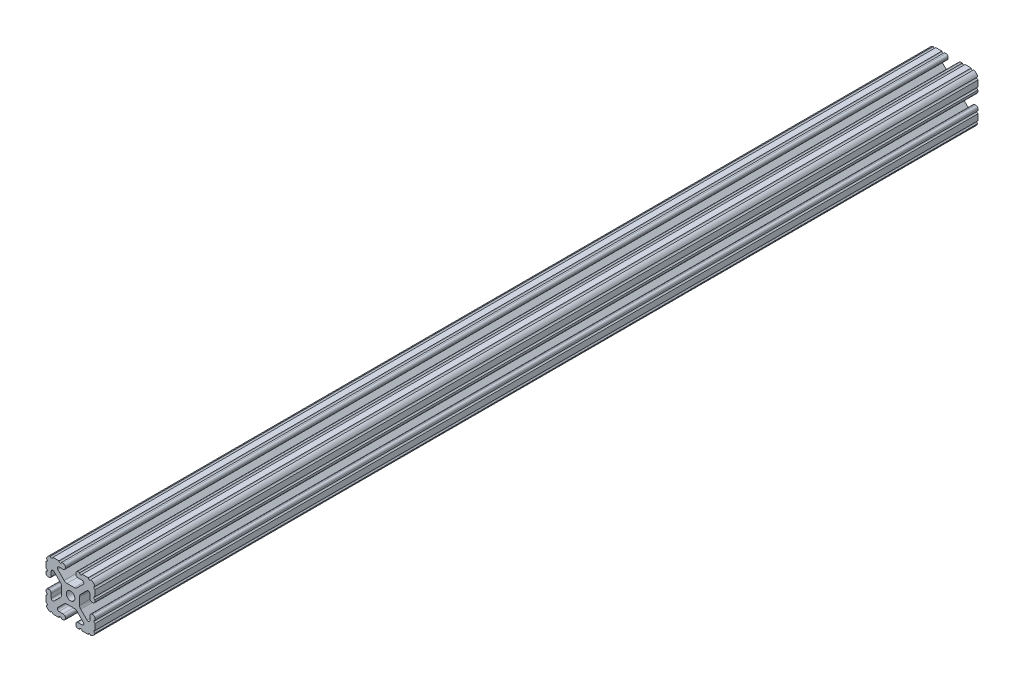
SolidWorks part; units mm, degrees
ref_plane "Front Plane" through (0, 0, 0) normal (0, 0, 1) x (1, 0, 0)
ref_plane "Top Plane" through (0, 0, 0) normal (0, 1, 0) x (1, 0, 0)
ref_plane "Right Plane" through (0, 0, 0) normal (1, 0, 0) x (0, 0, -1)
sketch "Sketch2" plane through (0, 0, 0) normal (0, 0, 1) x (1, 0, 0)
  line L0 (0, 19.05) -> (0, -19.05) construction
  line L1 (-19.05, 0) -> (19.05, 0) construction
  line L2 (4.064, -19.05) -> (19.05, -19.05)
  line L3 (19.05, -19.05) -> (19.05, -4.064)
  line L4 (4.064, -19.05) -> (4.064, -14.986)
  line L5 (4.064, -14.986) -> (12.1123, -14.986)
  line L6 (12.1123, -14.986) -> (4.1113, -6.985)
  line L7 (0, 0) -> (19.05, -19.05) construction
  line L8 (19.05, -4.064) -> (14.986, -4.064)
  line L9 (14.986, -4.064) -> (14.986, -12.1123)
  line L10 (14.986, -12.1123) -> (6.985, -4.1113)
  circle A0 centre (0, 0) radius 3.3274
  arc A1 (8.9963, -14.986) -> (9.909, -12.7826) centre (8.9963, -13.6953) ccw construction
  point P8 (0, -6.985)
  dimension "Center Hole Diameter" = 6.6548
  dimension "Rail Height" = 38.1
  dimension "Rail Width" = 38.1
  dimension "T-Slot Width" = 8.128
  dimension "Slot Inner Width" = 20.574
  dimension "Thickness" = 4.064
  dimension "Slot Depth" = 8.001
  dimension "D1" = 4.064
sketch "Sketch3" plane through (0, 0, 0) normal (1, 0, 0) x (0, 0, -1)
  line L0 (-342.5, -19.05) -> (342.5, -19.05) construction
  line L1 (-317.1, 0) -> (317.1, 0) construction
  dimension "Length" = 685
  dimension "D1" = 25.4
sketch "Sketch4" plane through (0, 0, 0) normal (0, 0, 1) x (1, 0, 0)
  line L0 (5.7912, -19.05) -> (14.3002, -19.05)
  line L1 (4.064, -19.05) -> (19.05, -19.05) construction
  line L2 (4.064, -19.05) -> (4.064, -14.986) construction
  line L3 (4.064, -14.986) -> (12.1123, -14.986) construction
  line L4 (4.064, -16.7132) -> (4.064, -17.3228)
  line L5 (5.7912, -14.986) -> (8.9963, -14.986)
  line L6 (0, -6.985) -> (2.833, -6.985)
  line L7 (12.1123, -14.986) -> (4.1113, -6.985) construction
  line L8 (5.0152, -7.8889) -> (9.909, -12.7826)
  line L9 (19.05, -19.05) -> (19.05, -4.064) construction
  line L10 (14.986, -12.1123) -> (6.985, -4.1113) construction
  line L11 (14.986, -4.064) -> (14.986, -12.1123) construction
  line L12 (14.986, -8.9963) -> (14.986, -5.7912)
  line L13 (19.05, -4.064) -> (14.986, -4.064) construction
  line L14 (16.7132, -4.064) -> (17.3228, -4.064)
  line L15 (19.05, -5.7912) -> (19.05, -14.3002)
  line L16 (12.7826, -9.909) -> (7.8889, -5.0152)
  line L17 (6.985, 0) -> (6.985, -2.833)
  line L18 (-19.05, 0) -> (19.05, 0) construction
  line L19 (0, -6.985) -> (0, -3.3274)
  line L20 (0, 19.05) -> (0, -19.05) construction
  line L21 (6.985, 0) -> (3.3274, 0)
  arc A0 (4.064, -17.3228) -> (5.7912, -19.05) centre (5.7912, -17.3228) ccw
  arc A2 (4.064, -16.7132) -> (5.7912, -14.986) centre (5.7912, -16.7132) cw
  arc A3 (8.9963, -14.986) -> (9.909, -12.7826) centre (8.9963, -13.6953) ccw
  arc A4 (2.833, -6.985) -> (5.0152, -7.8889) centre (2.833, -10.0711) cw
  arc A5 (14.3002, -19.05) -> (19.05, -14.3002) centre (14.3002, -14.3002) ccw
  arc A6 (12.7826, -9.909) -> (14.986, -8.9963) centre (13.6953, -8.9963) ccw
  arc A7 (14.986, -5.7912) -> (16.7132, -4.064) centre (16.7132, -5.7912) cw
  arc A8 (17.3228, -4.064) -> (19.05, -5.7912) centre (17.3228, -5.7912) cw
  arc A9 (7.8889, -5.0152) -> (6.985, -2.833) centre (10.0711, -2.833) cw
  circle A10 centre (0, 0) radius 3.3274 construction
  arc A11 (0, -3.3274) -> (3.3274, 0) centre (0, 0) ccw
  dimension "D1" = 4.7498
  dimension "D2" = 3.0861
  dimension "D3" = 1.7272
extrude "Boss-Extrude1" add sketch "Sketch4" along normal mid plane 685
sketch "Sketch5" plane through (0, 0, 0) normal (0, 0, 1) x (1, 0, 0)
  line L0 (4.064, -19.05) -> (19.05, -19.05) construction
  line L1 (5.7912, -14.986) -> (8.9963, -14.986) construction
  line L3 (0, 0) -> (19.05, -19.05) construction
  line L4 (8.9963, -14.986) -> (8.9963, -19.05) construction
  line L5 (12.1123, -14.986) -> (4.1113, -6.985) construction
  circle A0 centre (14.7395, -19.05) radius 1.016
  circle A1 centre (7.9803, -19.05) radius 1.016
  circle A2 centre (19.05, -14.7395) radius 1.016
  circle A3 centre (19.05, -7.9803) radius 1.016
  point P10 (7.3938, -14.986)
  point P12 (13.6953, -8.9963)
  dimension "D1" = 2.032
extrude "Cut-Extrude1" cut sketch "Sketch5" against normal through all both and the other way through all
mirror "Mirror1" about plane through (0, 0, 0) normal (1, 0, 0) of bodies 137 134
mirror "Mirror2" about plane through (0, 0, 0) normal (0, 1, 0) of bodies 135
equation "\"D1@Boss-Extrude1\"=\"Length@Sketch3\""
equation "\"D1@Sketch2\"=\"Thickness@Sketch2\""
equation "\"D2@Sketch4\"=\"Slot Inner Width@Sketch2\"*0.15"
equation "\"D1@Sketch4\"=\"D3@Sketch4\"*2.75"
equation "\"D3@Sketch4\"=\"Thickness@Sketch2\"*0.425"
equation "\"D1@Sketch5\"=\"Thickness@Sketch2\"*0.5"
